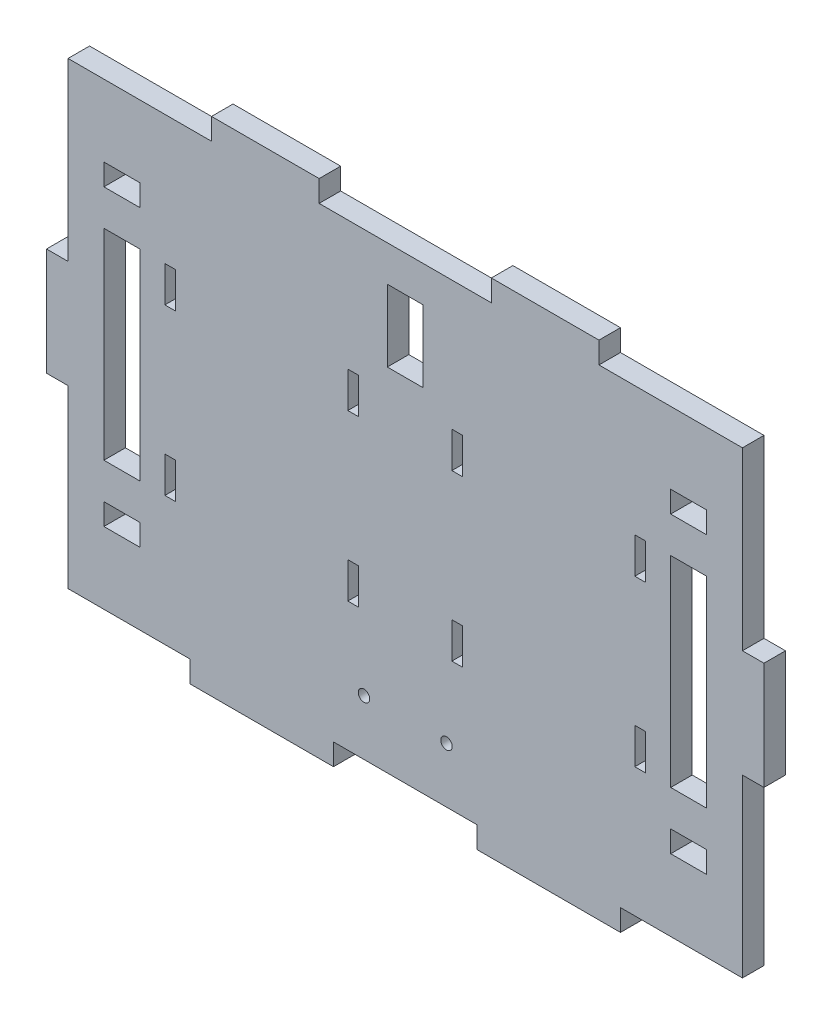
SolidWorks part; units mm, degrees
ref_plane "Plan de face" through (0, 0, 0) normal (0, 0, 1) x (1, 0, 0)
ref_plane "Plan de dessus" through (0, 0, 0) normal (0, 1, 0) x (1, 0, 0)
ref_plane "Plan de droite" through (0, 0, 0) normal (1, 0, 0) x (0, 0, -1)
sketch "Esquisse1" plane through (0, 0, 0) normal (0, 0, 1) x (1, 0, 0)
  line L0 (0, 64) -> (0, -64) construction
  line L1 (-94, 64) -> (-94, 15)
  line L2 (-94, 64) -> (-54, 64)
  line L3 (-94, -64) -> (-60, -64)
  line L4 (94, 64) -> (94, 15)
  line L5 (-94, 64) -> (94, -64) construction
  line L6 (-94, -64) -> (94, 64) construction
  line L7 (-24, 64) -> (24, 64)
  line L8 (54, 64) -> (54, 70)
  line L9 (-54, 64) -> (-54, 70)
  line L10 (-54, 70) -> (-24, 70)
  line L11 (-20, -64) -> (20, -64)
  line L12 (-24, 64) -> (-24, 70)
  line L13 (24, 64) -> (24, 70)
  line L14 (54, 70) -> (24, 70)
  line L15 (54, 64) -> (94, 64)
  line L16 (94, 15) -> (100, 15)
  line L17 (-94, 15) -> (-100, 15)
  line L18 (94, -15) -> (94, -64)
  line L19 (-94, -15) -> (-100, -15)
  line L20 (-100, 15) -> (-100, -15)
  line L21 (100, 15) -> (100, -15)
  line L22 (94, -15) -> (100, -15)
  line L23 (-94, -15) -> (-94, -64)
  line L24 (20, -64) -> (20, -70)
  line L25 (-60, -64) -> (-60, -70)
  line L26 (-60, -70) -> (-20, -70)
  line L27 (-20, -64) -> (-20, -70)
  line L28 (60, -70) -> (20, -70)
  line L29 (60, -64) -> (60, -70)
  line L30 (60, -64) -> (94, -64)
  point P0 (0, 0)
  dimension "D1" = 188
  dimension "D2" = 128
  dimension "D3" = 40
  dimension "D4" = 6
  dimension "D5" = 30
  dimension "D6" = 30
  dimension "D7" = 6
  dimension "D8" = 49
  dimension "D9" = 40
  dimension "D10" = 34
  dimension "D11" = 6
extrude "Boss.-Extru.3" add sketch "Esquisse1" along normal blind 6 contours L1 L17 L20 L19 L23 L3 L25 L26 L27 L11 L24 L28 L29 L30 L18 L22 L21 L16 L4 L15 L8 L14 L13 L7 L12 L10 L9 L2
sketch "Esquisse2" plane through (0, 0, 6) normal (0, 0, 1) x (1, 0, 0)
  line L0 (0, 64) -> (0, -64) construction
  line L1 (-94, -15) -> (-94, -64) construction
  line L2 (-67, -18) -> (-64, -18)
  line L3 (-67, -18) -> (-67, -28)
  line L4 (-67, -28) -> (-64, -28)
  line L5 (-67, 18) -> (-64, 18)
  line L6 (-67, 18) -> (-67, 28)
  line L7 (-67, 28) -> (-64, 28)
  line L8 (-64, 18) -> (-64, 28)
  line L9 (-16, -28) -> (-13, -28)
  line L10 (-16, -28) -> (-16, -18)
  line L11 (-16, -18) -> (-13, -18)
  line L12 (-13, -28) -> (-13, -18)
  line L13 (-16, 28) -> (-13, 28)
  line L14 (-16, 28) -> (-16, 18)
  line L15 (-16, 18) -> (-13, 18)
  line L16 (-13, 28) -> (-13, 18)
  line L20 (-64, -18) -> (-64, -28)
  line L21 (-94, -64) -> (-60, -64) construction
  line L22 (-94, 64) -> (-94, 15) construction
  line L23 (-94, 64) -> (-54, 64) construction
  line L24 (-20, -64) -> (20, -64) construction
  line L25 (-24, 64) -> (24, 64) construction
  line L26 (64, -18) -> (64, -28)
  line L27 (13, 28) -> (13, 18)
  line L28 (16, 18) -> (13, 18)
  line L29 (16, 28) -> (16, 18)
  line L30 (16, 28) -> (13, 28)
  line L31 (13, -28) -> (13, -18)
  line L32 (16, -18) -> (13, -18)
  line L33 (16, -28) -> (16, -18)
  line L34 (16, -28) -> (13, -28)
  line L35 (64, 18) -> (64, 28)
  line L36 (67, 28) -> (64, 28)
  line L37 (67, 18) -> (67, 28)
  line L38 (67, 18) -> (64, 18)
  line L39 (67, -28) -> (64, -28)
  line L40 (67, -18) -> (67, -28)
  line L41 (67, -18) -> (64, -18)
  dimension "D1" = 27
  dimension "D2" = 36
  dimension "D3" = 10
  dimension "D4" = 27
  dimension "D5" = 36
  dimension "D6" = 36
  dimension "D7" = 48
  dimension "D8" = 48
  dimension "D9" = 3
  dimension "D10" = 3
  dimension "D11" = 36
  dimension "D12" = 36
  dimension "D13" = 36
  dimension "D14" = 10
  dimension "D15" = 3
  dimension "D16" = 3
extrude "Enlèv. mat.-Extru.1" cut sketch "Esquisse2" against normal blind 10
sketch "Esquisse3" plane through (0, 0, 6) normal (0, 0, 1) x (1, 0, 0)
  line L0 (0, -64) -> (0, 64) construction
  line L1 (-84, -38) -> (-74, -38)
  line L2 (-74, -38) -> (-74, -44)
  line L3 (-74, -44) -> (-84, -44)
  line L4 (-84, -44) -> (-84, -38)
  line L5 (-94, -15) -> (-94, -64) construction
  line L6 (-94, -64) -> (-60, -64) construction
  line L7 (-20, -64) -> (20, -64) construction
  line L8 (-24, 64) -> (24, 64) construction
  line L9 (-100, 0) -> (100, 0) construction
  line L10 (-100, 15) -> (-100, -15) construction
  line L11 (100, 15) -> (100, -15) construction
  line L12 (84, -44) -> (84, -38)
  line L13 (74, -44) -> (84, -44)
  line L14 (74, -38) -> (74, -44)
  line L15 (84, -38) -> (74, -38)
  line L16 (84, 38) -> (74, 38)
  line L17 (74, 38) -> (74, 44)
  line L18 (74, 44) -> (84, 44)
  line L19 (84, 44) -> (84, 38)
  line L20 (-84, 44) -> (-84, 38)
  line L21 (-74, 44) -> (-84, 44)
  line L22 (-74, 38) -> (-74, 44)
  line L23 (-84, 38) -> (-74, 38)
  dimension "D1" = 10
  dimension "D2" = 10
  dimension "D3" = 6
  dimension "D4" = 20
extrude "Enlèv. mat.-Extru.2" cut sketch "Esquisse3" against normal blind 6
sketch "Esquisse4" plane through (0, 0, 0) normal (0, 0, -1) x (-1, 0, 0)
  line L0 (74, -38) -> (84, -38) construction
  line L1 (74, 28) -> (84, 28)
  line L2 (74, 28) -> (74, -28)
  line L3 (74, -28) -> (84, -28)
  line L4 (84, 28) -> (84, -28)
  line L5 (-84, 28) -> (-74, 28)
  line L6 (-84, 28) -> (-84, -28)
  line L7 (-84, -28) -> (-74, -28)
  line L8 (-74, 28) -> (-74, -28)
  line L9 (-84, -38) -> (-74, -38) construction
  line L10 (-74, 38) -> (-84, 38) construction
  line L11 (-94, -15) -> (-94, -64) construction
  line L12 (-67, -28) -> (-67, -18) construction
  line L13 (94, -15) -> (94, -64) construction
  dimension "D1" = 10
  dimension "D2" = 10
  dimension "D3" = 10
  dimension "D4" = 10
  dimension "D5" = 56
  dimension "D6" = 56
  dimension "D7" = 10
  dimension "D8" = 10
  dimension "D9" = 7
  dimension "D10" = 10
extrude "Enlèv. mat.-Extru.3" cut sketch "Esquisse4" against normal blind 6
sketch "Esquisse5" plane through (0, 0, 0) normal (0, 0, -1) x (-1, 0, 0)
  line L0 (24, 64) -> (-24, 64) construction
  line L1 (-5, 54) -> (5, 54)
  line L2 (-5, 54) -> (-5, 34)
  line L3 (-5, 34) -> (5, 34)
  line L4 (5, 54) -> (5, 34)
  point P6 (0, 64)
  dimension "D1" = 10
  dimension "D2" = 20
  dimension "D3" = 10
  dimension "D4" = 5
extrude "Enlèv. mat.-Extru.4" cut sketch "Esquisse5" against normal through all
sketch "Esquisse6" plane through (0, 0, 0) normal (0, 0, -1) x (-1, 0, 0)
  line L0 (20, -64) -> (-20, -64) construction
  line L1 (-20, -64) -> (-20, -70) construction
  circle A0 centre (-11.5, -48.6) radius 1.6
  circle A1 centre (11.5, -48.6) radius 1.6
  point P6 (-20, -67)
  dimension "D1" = 3.2
  dimension "D2" = 3.2
  dimension "D3" = 15.4
  dimension "D4" = 15.4
  dimension "D5" = 23
  dimension "D6" = 8.5
extrude "Enlèv. mat.-Extru.5" cut sketch "Esquisse6" against normal through all
